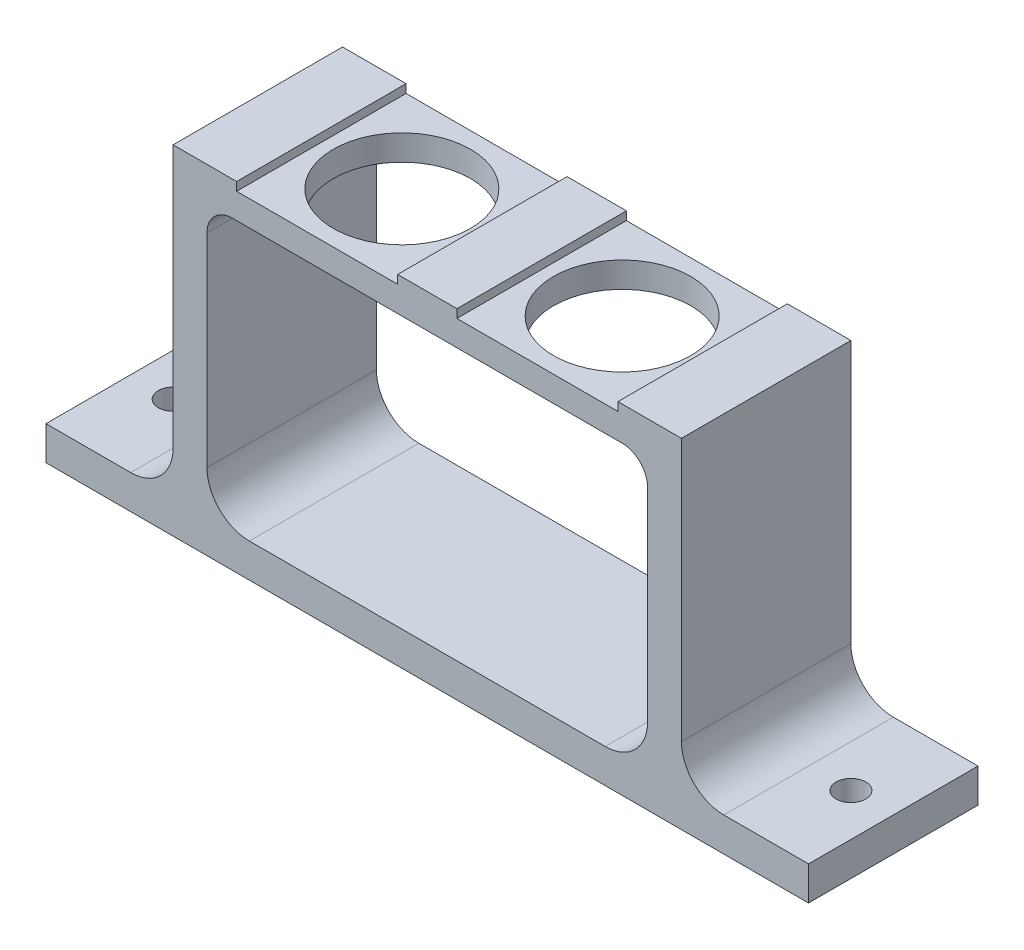
SolidWorks part; units mm, degrees
ref_plane "前视基准面" through (0, 0, 0) normal (0, 0, 1) x (1, 0, 0)
ref_plane "上视基准面" through (0, 0, 0) normal (0, 1, 0) x (1, 0, 0)
ref_plane "右视基准面" through (0, 0, 0) normal (1, 0, 0) x (0, 0, -1)
sketch "草图1" plane through (0, 0, 0) normal (0, 1, 0) x (1, 0, 0)
  line L0 (45, 10) -> (45, 29.8353) construction
  line L1 (0, 0) -> (90, 0)
  line L2 (0, 0) -> (0, 20)
  line L3 (0, 20) -> (90, 20)
  line L4 (90, 0) -> (90, 20)
  line L5 (0, 0) -> (90, 20) construction
  line L6 (0, 20) -> (90, 0) construction
  circle A0 centre (85, 10) radius 1.75
  circle A3 centre (5, 10) radius 1.75
  point P4 (45, 10)
  dimension "D4" = 5
  dimension "D5" = 3.5
  dimension "D7" = 10
  dimension "D1" = 20
  dimension "D2" = 90
extrude "凸台-拉伸1" add sketch "草图1" along normal blind 4
sketch "草图2" plane through (0, 4, 0) normal (0, 1, 0) x (1, 0, 0)
  line L0 (90, 20) -> (0, 20) construction
  line L1 (15, 20) -> (19, 20)
  line L2 (15, 20) -> (15, 0)
  line L3 (15, 0) -> (19, 0)
  line L4 (75, 20) -> (75, 0)
  line L5 (15, 20) -> (19, 18.6667) construction
  line L6 (15, 0) -> (19, 1.3333) construction
  line L7 (0, 0) -> (90, 0) construction
  line L8 (19, 20) -> (19, 0)
  line L9 (71, 0) -> (71, 20)
  line L10 (71, 20) -> (75, 20)
  line L11 (71, 1.3333) -> (75, 0) construction
  line L12 (71, 18.6667) -> (75, 20) construction
  line L13 (71, 0) -> (75, 0)
  circle A2 centre (5, 10) radius 1.75 construction
  circle A3 centre (85, 10) radius 1.75 construction
  point P4 (45, 10)
  dimension "D1" = 10
  dimension "D2" = 10
  dimension "D3" = 4
  dimension "D4" = 4
extrude "凸台-拉伸2" add sketch "草图2" along normal blind 32
sketch "草图3" plane through (0, 36, 0) normal (0, 1, 0) x (1, 0, 0)
  line L0 (19, 0) -> (19, 20) construction
  line L1 (15, 20) -> (75, 20)
  line L2 (15, 20) -> (15, 0)
  line L3 (15, 0) -> (75, 0)
  line L4 (75, 20) -> (75, 0)
  line L5 (15, 20) -> (75, 0) construction
  line L6 (15, 0) -> (75, 20) construction
  line L7 (71, 20) -> (71, 0) construction
  circle A0 centre (32, 10) radius 8.1
  circle A1 centre (58, 10) radius 8.1
  point P4 (45, 10)
  dimension "D1" = 16.2
  dimension "D2" = 16.2
  dimension "D3" = 13
  dimension "D4" = 13
  dimension "D5" = 10
  dimension "D6" = 26
extrude "凸台-拉伸3" add sketch "草图3" along normal blind 4
fillet "圆角1" radius 5 4 edges at (75, 4, -10) (71, 4, -10) (15, 4, -10) (19, 4, -10)
fillet "圆角2" radius 3 2 edges at (71, 36, -10) (19, 36, -10)
sketch "草图4" plane through (0, 40, 0) normal (0, 1, 0) x (1, 0, 0)
  line L1 (22.5, 0) -> (41.5, 0)
  line L2 (22.5, 0) -> (22.5, 20)
  line L3 (22.5, 20) -> (41.5, 20)
  line L4 (41.5, 0) -> (41.5, 20)
  line L5 (22.5, 0) -> (41.5, 20) construction
  line L6 (22.5, 20) -> (41.5, 0) construction
  line L7 (48.5, 0) -> (67.5, 0)
  line L8 (48.5, 0) -> (48.5, 20)
  line L9 (48.5, 20) -> (67.5, 20)
  line L10 (67.5, 0) -> (67.5, 20)
  line L11 (48.5, 0) -> (67.5, 20) construction
  line L12 (48.5, 20) -> (67.5, 0) construction
  point P0 (32, 10)
  point P6 (58, 10)
  dimension "D1" = 20
  dimension "D2" = 19
  dimension "D3" = 19
  dimension "D4" = 20
extrude "切除-拉伸1" cut sketch "草图4" against normal blind 1
